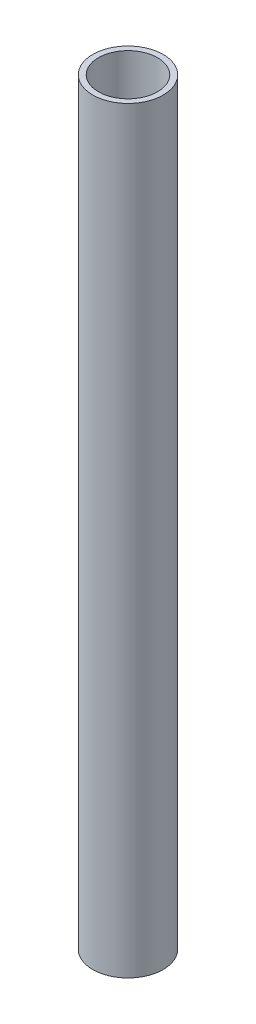
SolidWorks part; units mm, degrees
material "7075-T6 (SN)"
ref_plane "Alzado" through (0, 0, 0) normal (0, 0, 1) x (1, 0, 0)
ref_plane "Planta" through (0, 0, 0) normal (0, 1, 0) x (1, 0, 0)
ref_plane "Vista lateral" through (0, 0, 0) normal (1, 0, 0) x (0, 0, -1)
sketch "Croquis1" plane through (0, 0, 0) normal (0, 1, 0) x (1, 0, 0)
  circle A0 centre (0, 0) radius 12.5
  circle A1 centre (0, 0) radius 10.5
  dimension "D1" = 25
  dimension "D2" = 2
extrude "Saliente-Extruir1" add sketch "Croquis1" along normal blind 269
